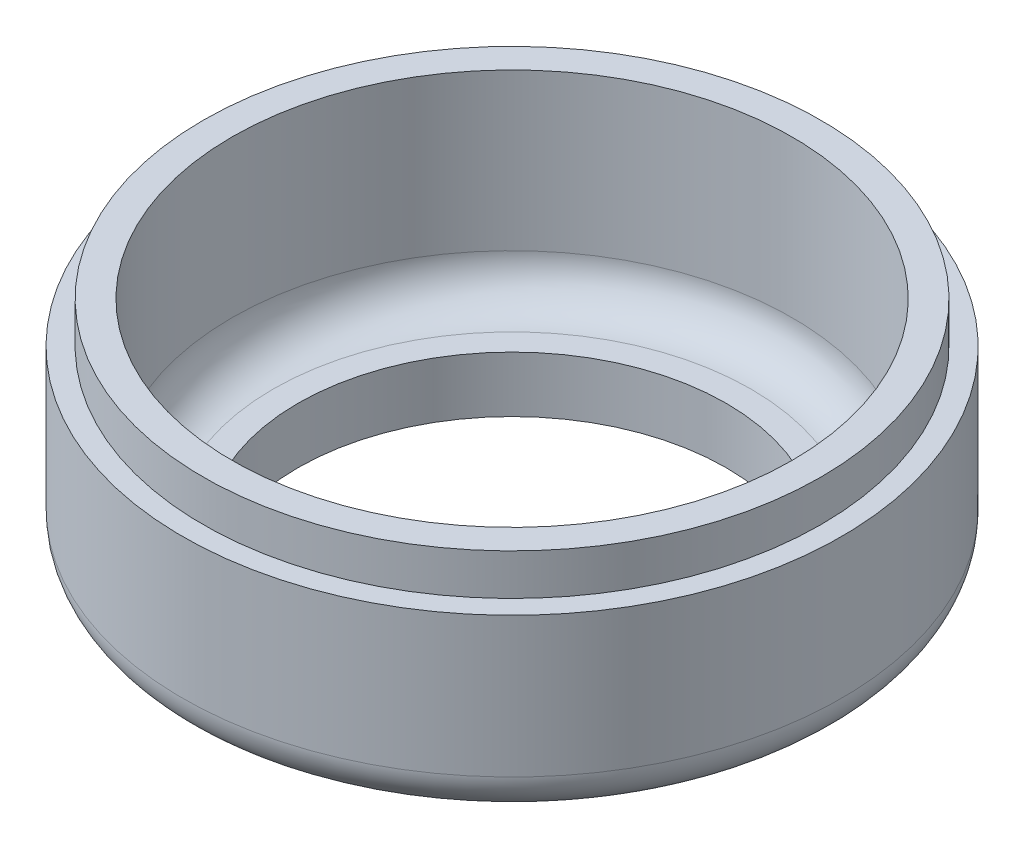
SolidWorks part; units mm, degrees
ref_plane "Front Plane" through (0, 0, 0) normal (0, 0, 1) x (1, 0, 0)
ref_plane "Top Plane" through (0, 0, 0) normal (0, 1, 0) x (1, 0, 0)
ref_plane "Right Plane" through (0, 0, 0) normal (1, 0, 0) x (0, 0, -1)
sketch "Sketch1" plane through (0, 0, 0) normal (0, 0, 1) x (1, 0, 0)
  line L0 (0, 133.0434) -> (0, -133.0434) construction
  line L1 (-176.879, 0) -> (183.3225, 0) construction
  line L2 (-40, 8.797) -> (-40, -8.203)
  line L3 (-35, -13.203) -> (-29, -13.203)
  line L4 (-34, 13.797) -> (-34, -5.203)
  line L6 (-37.5, 13.797) -> (-34, 13.797)
  line L8 (-37.5, 13.797) -> (-37.5, 8.797)
  line L9 (-37.5, 8.797) -> (-40, 8.797)
  line L10 (-29, -13.203) -> (-29, -16.9803)
  line L11 (-29, -16.9803) -> (-26, -16.9803)
  line L13 (-29, -10.203) -> (-26, -10.203)
  line L15 (-26, -16.9803) -> (-26, -10.203)
  arc A0 (-34, -5.203) -> (-29, -10.203) centre (-29, -5.203) ccw
  arc A1 (-40, -8.203) -> (-35, -13.203) centre (-35, -8.203) ccw
  dimension "D2" = 52
  dimension "D6" = 5
  dimension "D7" = 5
  dimension "D1" = 5
  dimension "D3" = 68
  dimension "D4" = 75
  dimension "D5" = 80
  dimension "D8" = 58
  dimension "D9" = 3
revolve "Revolve1" add sketch "Sketch1" angle 360 about L0
